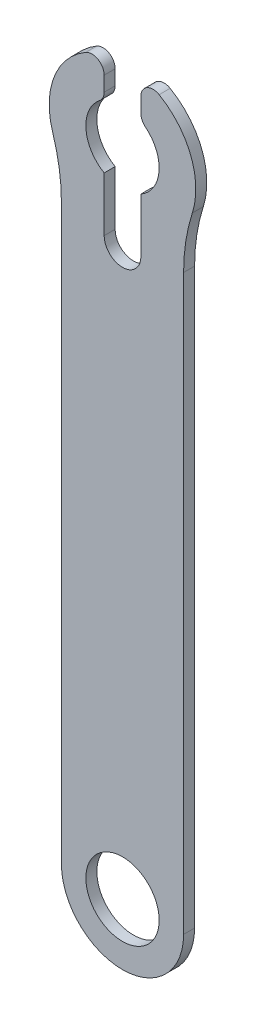
SolidWorks part; units mm, degrees
ref_plane "Plan de face" through (0, 0, 0) normal (0, 0, 1) x (1, 0, 0)
ref_plane "Plan de dessus" through (0, 0, 0) normal (0, 1, 0) x (1, 0, 0)
ref_plane "Plan de droite" through (0, 0, 0) normal (1, 0, 0) x (0, 0, -1)
sketch "Esquisse1" plane through (0, 0, 0) normal (0, 0, 1) x (1, 0, 0)
  line L0 (-1.5, 5.8095) -> (-1.5, 2.5981)
  line L1 (0, 0) -> (0, 9.5605) construction
  line L2 (1.5, 5.8095) -> (1.5, 2.5981)
  line L3 (-5, -3.3166) -> (-5, -53.3166)
  line L4 (5, -3.3166) -> (5, -53.3166)
  line L5 (0, 1.0421) -> (0, -7.0421) construction
  line L6 (1.5, 1.0421) -> (1.5, -7.0421)
  line L7 (-1.5, 1.0421) -> (-1.5, -7.0421)
  arc A0 (-1.5, 2.5981) -> (1.5, 2.5981) centre (0, 0) ccw
  arc A1 (5, -3.3166) -> (1.5, 5.8095) centre (0, 0) ccw
  arc A2 (-5, -53.3166) -> (5, -53.3166) centre (0, -53.3166) ccw
  arc A3 (-5, -3.3166) -> (5, -3.3166) centre (0, 0) ccw construction
  circle A4 centre (0, 0) radius 6 construction
  arc A5 (1.5, 5.8095) -> (0, 6) centre (0, 0) ccw construction
  arc A6 (-1.5, 5.8095) -> (-5, -3.3166) centre (0, 0) ccw
  arc A7 (0, 6) -> (-1.5, 5.8095) centre (0, 0) ccw construction
  arc A8 (1.5, 2.5981) -> (-0.1629, 2.9956) centre (0, 0) ccw construction
  circle A9 centre (0, 0) radius 3 construction
  arc A10 (-0.1629, 2.9956) -> (-1.5, 2.5981) centre (0, 0) ccw construction
  circle A11 centre (0, -53.3166) radius 3
  arc A12 (1.5, 1.0421) -> (-1.5, 1.0421) centre (0, 1.0421) ccw
  arc A13 (-1.5, -7.0421) -> (1.5, -7.0421) centre (0, -7.0421) ccw
  point P20 (0, -3)
  point P25 (0, 3)
  point P26 (-0.1629, 2.9956)
  dimension "D1" = 6
  dimension "D3" = 1.5
  dimension "D4" = 5
  dimension "D5" = 50
  dimension "D6" = 3
  dimension "D2" = 3
extrude "Boss.-Extru.1" add sketch "Esquisse1" along normal blind 0.9 contours A13 L7 A0 L0 A6 L3 A2 L4 A1 L2 L6 A11
fillet "Congé1" radius 15 2 edges at (5, -3.3166, 0.45) (-5, -3.3166, 0.45)
fillet "Congé2" radius 1 4 edges at (1.5, 2.5981, 0.45) (-1.5, 2.5981, 0.45) (1.5, 5.8095, 0.45) (-1.5, 5.8095, 0.45)
